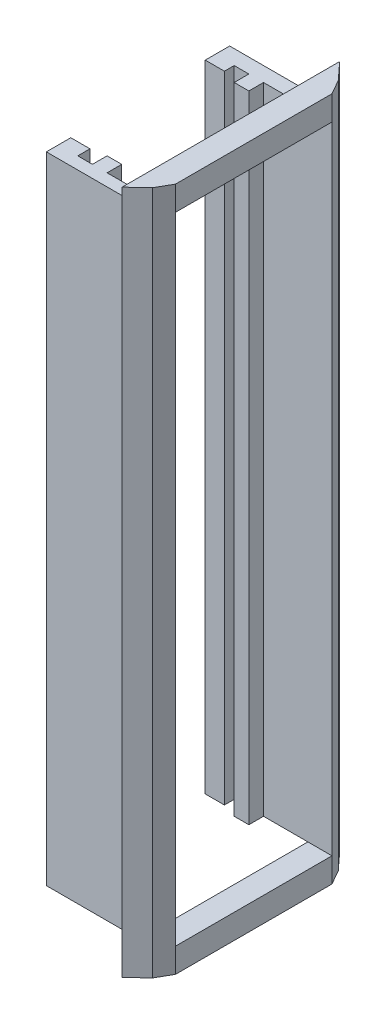
SolidWorks part; units mm, degrees
ref_plane "Front" through (0, 0, 0) normal (0, 0, 1) x (1, 0, 0)
ref_plane "Top" through (0, 0, 0) normal (0, 1, 0) x (1, 0, 0)
ref_plane "Right" through (0, 0, 0) normal (1, 0, 0) x (0, 0, -1)
sketch "Sketch1" plane through (0, 0, 0) normal (0, 1, 0) x (1, 0, 0)
  line L0 (0, -3) -> (0, 29)
  line L1 (0, -3) -> (3, -3)
  line L2 (3, -3) -> (3, 0)
  line L3 (3, 0) -> (6, 0)
  line L4 (6, 0) -> (6, -3)
  line L5 (6, -3) -> (20, -3)
  line L6 (0, 29) -> (3, 29)
  line L7 (-3.9246, -5.5) -> (-3.9246, 32)
  line L8 (-3.9246, 32) -> (15.0754, 32)
  line L9 (-3.9246, -5.5) -> (15.0754, -5.5)
  line L10 (15.0754, 32) -> (15.0754, 35.5)
  line L11 (3, 29) -> (3, 26)
  line L12 (3, 26) -> (6, 26)
  line L13 (6, 26) -> (6, 29)
  line L14 (6, 29) -> (20, 29)
  line L15 (15.0754, 35.5) -> (18.2906, 32)
  line L19 (15.0754, -5.5) -> (15.0754, -9)
  line L20 (15.0754, -9) -> (18.2906, -6)
  line L21 (18.2906, -6) -> (20, -3)
  line L22 (18.2906, 32) -> (20, 29)
  dimension "D1" = 14
extrude "Boss-Extrude2" add sketch "Sketch1" along normal blind 130
sketch "Sketch2" plane through (0, 130, 0) normal (0, 1, 0) x (1, 0, 0)
  line L0 (15.0754, 35.5) -> (15.0754, -9)
  line L1 (15.0754, -9) -> (18.2906, -6)
  line L2 (18.2906, -6) -> (20, -3)
  line L3 (20, -3) -> (20, 29)
  line L4 (20, 29) -> (18.2906, 32)
  line L5 (18.2906, 32) -> (15.0754, 35.5)
extrude "Boss-Extrude3" add sketch "Sketch2" along normal blind 5
sketch "Sketch3" plane through (0, 0, 0) normal (0, -1, 0) x (1, 0, 0)
  line L0 (15.0754, 9) -> (15.0754, -35.5)
  line L1 (15.0754, -35.5) -> (18.2906, -32)
  line L2 (18.2906, -32) -> (20, -29)
  line L3 (20, -29) -> (20, 3)
  line L4 (20, 3) -> (18.2906, 6)
  line L5 (18.2906, 6) -> (15.0754, 9)
extrude "Boss-Extrude4" add sketch "Sketch3" along normal blind 5
sketch "Sketch4" plane through (-3.9246, 0, 0) normal (-1, 0, 0) x (0, 0, 1)
  line L0 (0.5, 125) -> (0.5, 130)
  line L1 (-32, 130) -> (5.5, 130) construction
  line L2 (-27, 125) -> (-27, 5)
  line L3 (0.5, 130) -> (-27, 130)
  line L4 (-27, 130) -> (-27, 0)
  line L5 (-32, 0) -> (5.5, 0) construction
  line L7 (-27, 0) -> (0.5, 0)
  line L9 (3, 0) -> (-29, 0) construction
  line L10 (0.5, 125) -> (0.5, 5)
  line L11 (0.5, 0) -> (0.5, 5)
  line M5 (-32, 0) -> (5.5, 0)
  line M7 (5.5, 130) -> (-32, 130)
extrude "Cut-Extrude2" cut sketch "Sketch4" against normal blind 6 contours L11 L10 L0 L4 L2 M5 M7
